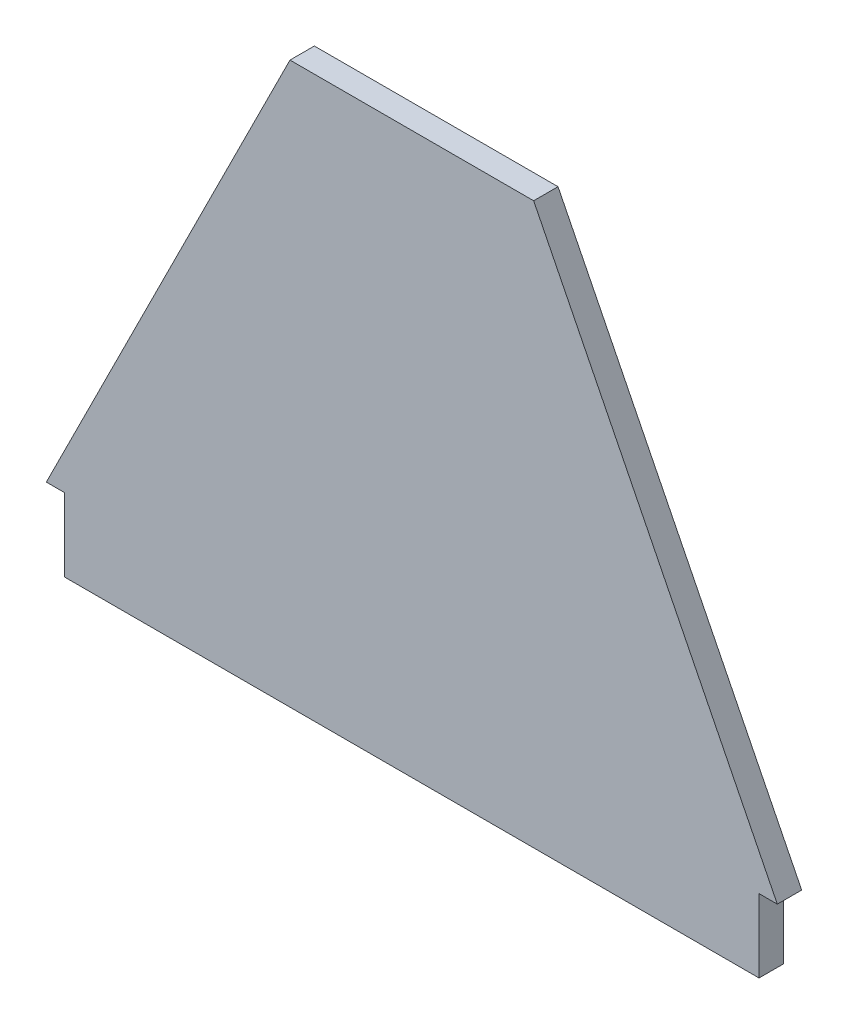
SolidWorks part; units mm, degrees
material "Balsa"
ref_plane "Front Plane" through (0, 0, 0) normal (0, 0, 1) x (1, 0, 0)
ref_plane "Top Plane" through (0, 0, 0) normal (0, 1, 0) x (1, 0, 0)
ref_plane "Right Plane" through (0, 0, 0) normal (1, 0, 0) x (0, 0, -1)
sketch "Sketch1" plane through (0, 0, 0) normal (0, 0, 1) x (1, 0, 0)
  line L0 (75, 11.7259) -> (71.25, 11.7259)
  line L1 (0, -3.2741) -> (0, 111.7259) construction
  line L2 (25, 111.7259) -> (-25, 111.7259)
  line L3 (-75, 11.7259) -> (-25, 111.7259)
  line L4 (75, 11.7259) -> (25, 111.7259)
  line L5 (71.25, 11.7259) -> (71.25, -3.2741)
  line L6 (71.25, -3.2741) -> (-71.25, -3.2741)
  line L7 (-71.25, -3.2741) -> (-71.25, 11.7259)
  line L8 (-71.25, 11.7259) -> (-75, 11.7259)
  point P3 (0, -3.2741)
  point P4 (0, 0)
  point P10 (0, 111.7259)
  dimension "D1" = 50
  dimension "100" = 100
  dimension "D3" = 75
  dimension "D4" = 75
  dimension "D5" = 142.5
  dimension "D6" = 15
extrude "Boss-Extrude1" add sketch "Sketch1" along normal blind 5
